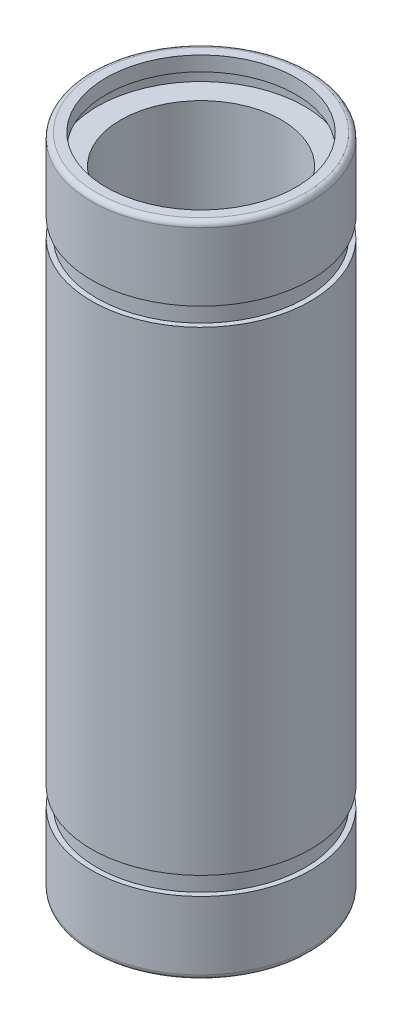
SolidWorks part; units mm, degrees
material "ASTM A36 Steel"
ref_plane "Front" through (0, 0, 0) normal (0, 0, 1) x (1, 0, 0)
ref_plane "Top" through (0, 0, 0) normal (0, 1, 0) x (1, 0, 0)
ref_plane "Right" through (0, 0, 0) normal (1, 0, 0) x (0, 0, -1)
sketch "Sketch1" plane through (0, 0, 0) normal (1, 0, 0) x (0, -1, 0)
  line L0 (22.5, 7.15) -> (22.5, 6.5)
  line L1 (22.5, 6.5) -> (21.5, 6.5)
  line L2 (21.5, 6.5) -> (21.5, 7.1)
  line L3 (22.15, 7.5) -> (17.5, 7.5)
  line L4 (21.5, 7.1) -> (20.5, 7.1)
  line L5 (20.5, 7.1) -> (20.5, 5.5)
  line L6 (17.5, 7.15) -> (17.5, 7.5)
  line L7 (16.25, 7.5) -> (-16.25, 7.5)
  line L8 (-16.25, 7.5) -> (-16.25, 7.15)
  line L9 (-16.25, 7.15) -> (-17.5, 7.15)
  line L10 (-17.5, 7.15) -> (-17.5, 7.5)
  line L11 (-17.5, 7.5) -> (-22.15, 7.5)
  line L12 (-22.5, 7.15) -> (-22.5, 6.5)
  line L13 (-22.5, 6.5) -> (-21.5, 6.5)
  line L14 (-21.5, 6.5) -> (-21.5, 7.1)
  line L15 (-21.5, 7.1) -> (-20.5, 7.1)
  line L16 (-20.5, 7.1) -> (-20.5, 5.5)
  line L17 (-20.5, 5.5) -> (20.5, 5.5)
  line L18 (20.5, 5.5) -> (20.5, 7.1)
  line L19 (16.25, 7.15) -> (17.5, 7.15)
  line L20 (-12, 0) -> (12, 0) construction
  line L21 (0, 5.0091) -> (0, 0) construction
  line L22 (16.25, 7.5) -> (16.25, 7.15)
  arc A0 (22.15, 7.5) -> (22.5, 7.15) centre (22.15, 7.15) cw
  arc A1 (-22.15, 7.5) -> (-22.5, 7.15) centre (-22.15, 7.15) ccw
  dimension "D11" = 0.35
  dimension "D1" = 11
  dimension "D2" = 15
  dimension "D3" = 45
  dimension "D4" = 5
  dimension "D5" = 1.25
  dimension "D6" = 0.35
  dimension "D7" = 1.6
  dimension "D8" = 1
  dimension "D9" = 13
  dimension "D10" = 1
revolve "Revolve1" add sketch "Sketch1" angle 360 about L20
